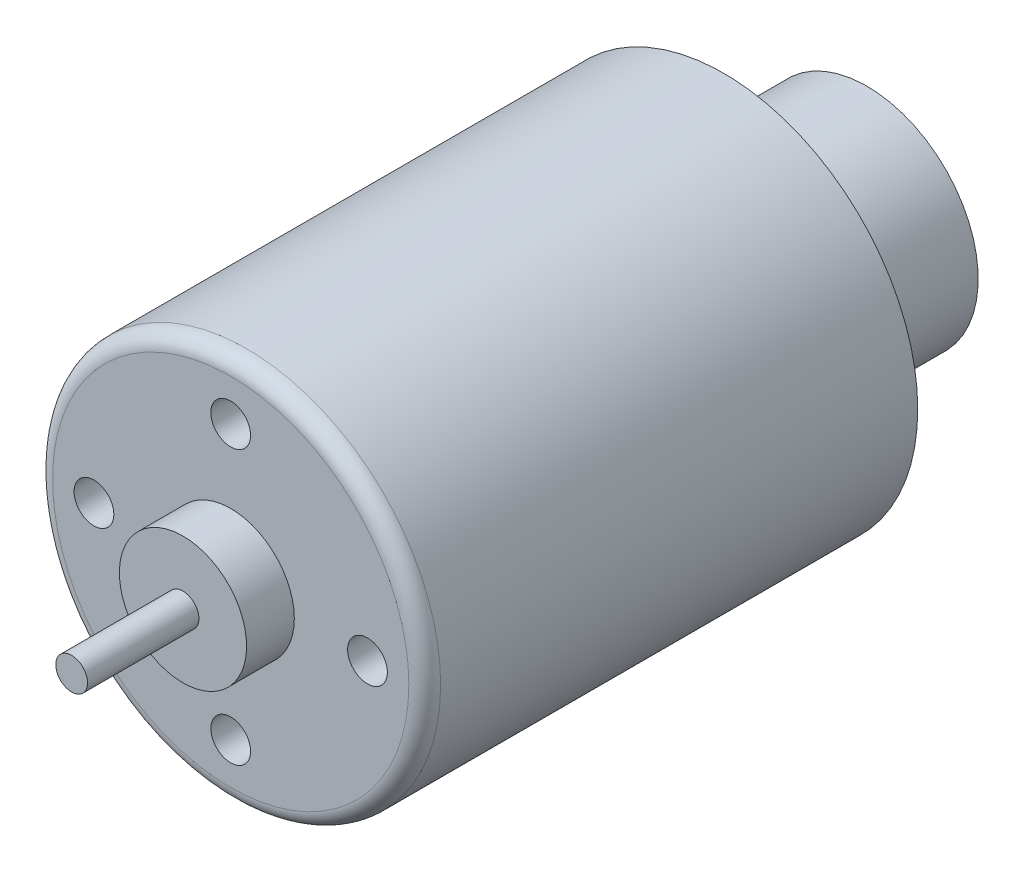
SolidWorks part; units mm, degrees
ref_plane "Plano frontal" through (0, 0, 0) normal (0, 0, 1) x (1, 0, 0)
ref_plane "Plano superior" through (0, 0, 0) normal (0, 1, 0) x (1, 0, 0)
ref_plane "Plano direito" through (0, 0, 0) normal (1, 0, 0) x (0, 0, -1)
sketch "Esboço1" plane through (0, 0, 0) normal (0, 0, 1) x (1, 0, 0)
  circle A0 centre (0, 0) radius 12.2
  dimension "D1" = 24.4
extrude "Ressalto-extrusão1" add sketch "Esboço1" along normal blind 31
sketch "Esboço2" plane through (0, 0, 31) normal (0, 0, 1) x (1, 0, 0)
  line L0 (-8.6, 0) -> (8.6, 0) construction
  line L1 (0, 8.6) -> (0, -8.6) construction
  point P3 (0, 0)
  point P8 (0, 0)
  dimension "D1" = 17.2
  dimension "D2" = 17.2
hole_wizard "Broca de rosquear para tarraxa de M31" positions "3DSketch2" profile "Esboço4" hole size "M3" standard "ISO"
sketch3d "3DSketch2"
  point P0 (-8.6, 0, 31)
  point P3 (0, 8.6, 31)
  point P6 (8.6, 0, 31)
  point P9 (0, -8.6, 31)
sketch "Esboço4" plane through (-8.6, 0, 31) normal (1, 0, 0) x (0, -1, 0)
  line L0 (0, 0) -> (0, 3.7511)
  line L1 (0, 3.7511) -> (1.25, 3)
  line L2 (1.25, 3) -> (1.25, 0)
  line L5 (1.25, 0) -> (0, 0)
  line L10 (0, 3.7511) -> (-1.25, 3) construction
  line L11 (0, -6.35) -> (0, 107.95) construction
  dimension "Hole Dia." = 2.5
  dimension "Hole Depth" = 3
  dimension "Drill Angle" = 118
sketch "Esboço5" plane through (0, 0, 31) normal (0, 0, 1) x (1, 0, 0)
  circle A0 centre (0, 0) radius 4
  dimension "D1" = 8
extrude "Ressalto-extrusão2" add sketch "Esboço5" along normal blind 3
sketch "Esboço6" plane through (0, 0, 34) normal (0, 0, 1) x (1, 0, 0)
  circle A0 centre (0, 0) radius 1
  dimension "D1" = 2
extrude "Ressalto-extrusão3" add sketch "Esboço6" along normal blind 7
sketch "Esboço7" plane through (0, 0, 0) normal (0, 0, -1) x (-1, 0, 0)
  circle A0 centre (0, 0) radius 7
  dimension "D1" = 14
extrude "Ressalto-extrusão4" add sketch "Esboço7" along normal blind 9
fillet "Filete1" radius 1 1 edges at (12.2, 0, 31)
